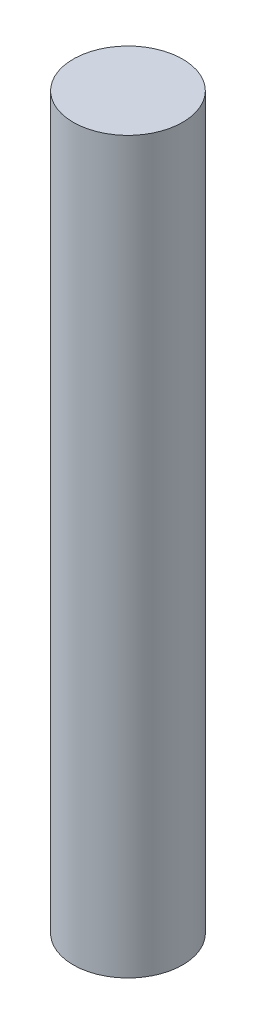
SolidWorks part; units mm, degrees
material "3.0255 (EN-AW 1350A)"
ref_plane "정면" through (0, 0, 0) normal (0, 0, 1) x (1, 0, 0)
ref_plane "윗면" through (0, 0, 0) normal (0, 1, 0) x (1, 0, 0)
ref_plane "우측면" through (0, 0, 0) normal (1, 0, 0) x (0, 0, -1)
sketch "스케치1" plane through (0, 0, 0) normal (0, 1, 0) x (1, 0, 0)
  circle A0 centre (0, 0) radius 7.5
  dimension "D1" = 15
extrude "보스-돌출1" add sketch "스케치1" along normal blind 100
sketch "스케치2" plane through (0, 0, 0) normal (0, 0, 1) x (1, 0, 0)
  line L0 (-7.5, 0) -> (7.5, 0) construction
  circle A0 centre (0, 40) radius 2
  circle A1 centre (0, 60) radius 2
  point P4 (0, 0)
  dimension "D2" = 4
  dimension "D3" = 4
  dimension "D1" = 40
  dimension "D4" = 60
extrude "컷-돌출1" cut sketch "스케치2" against normal blind 10
